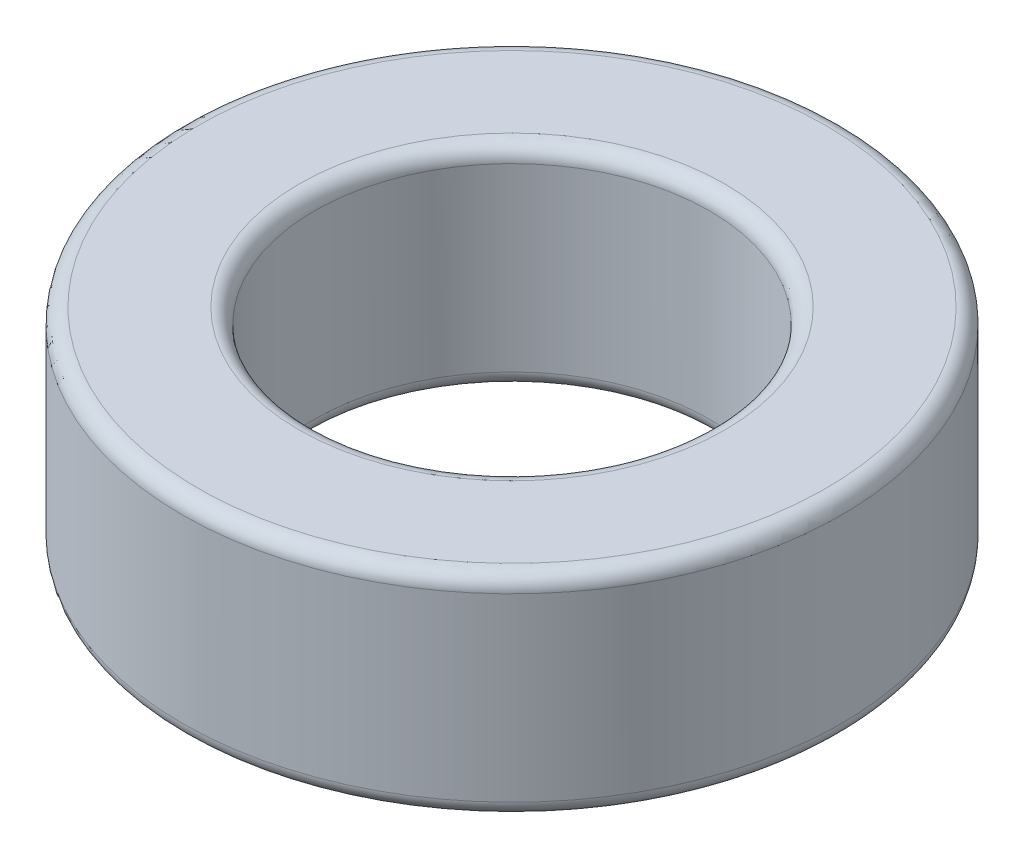
SolidWorks part; units mm, degrees
ref_plane "Front Plane" through (0, 0, 0) normal (0, 0, 1) x (1, 0, 0)
ref_plane "Top Plane" through (0, 0, 0) normal (0, 1, 0) x (1, 0, 0)
ref_plane "Right Plane" through (0, 0, 0) normal (1, 0, 0) x (0, 0, -1)
sketch "Sketch1" plane through (0, 0, 0) normal (0, 0, 1) x (1, 0, 0)
  line L0 (0, 15.8866) -> (0, -19.4169) construction
  line L2 (12.75, 6.825) -> (21.275, 6.825)
  line L3 (12.75, 6.825) -> (12.75, -6.825)
  line L4 (12.75, -6.825) -> (21.275, -6.825)
  line L5 (21.275, 6.825) -> (21.275, -6.825)
  line L6 (12.75, 6.825) -> (21.275, -6.825) construction
  line L7 (12.75, -6.825) -> (21.275, 6.825) construction
  point P3 (17.0125, 0)
  dimension "D1" = 42.55
  dimension "D2" = 25.5
  dimension "D3" = 13.65
revolve "Revolve1" add sketch "Sketch1" angle 360 about L0
fillet "Fillet1" radius 1 4 edges at (0, -6.825, 12.75) (0, -6.825, 21.275) (0, 6.825, 21.275) (0, 6.825, 12.75)
